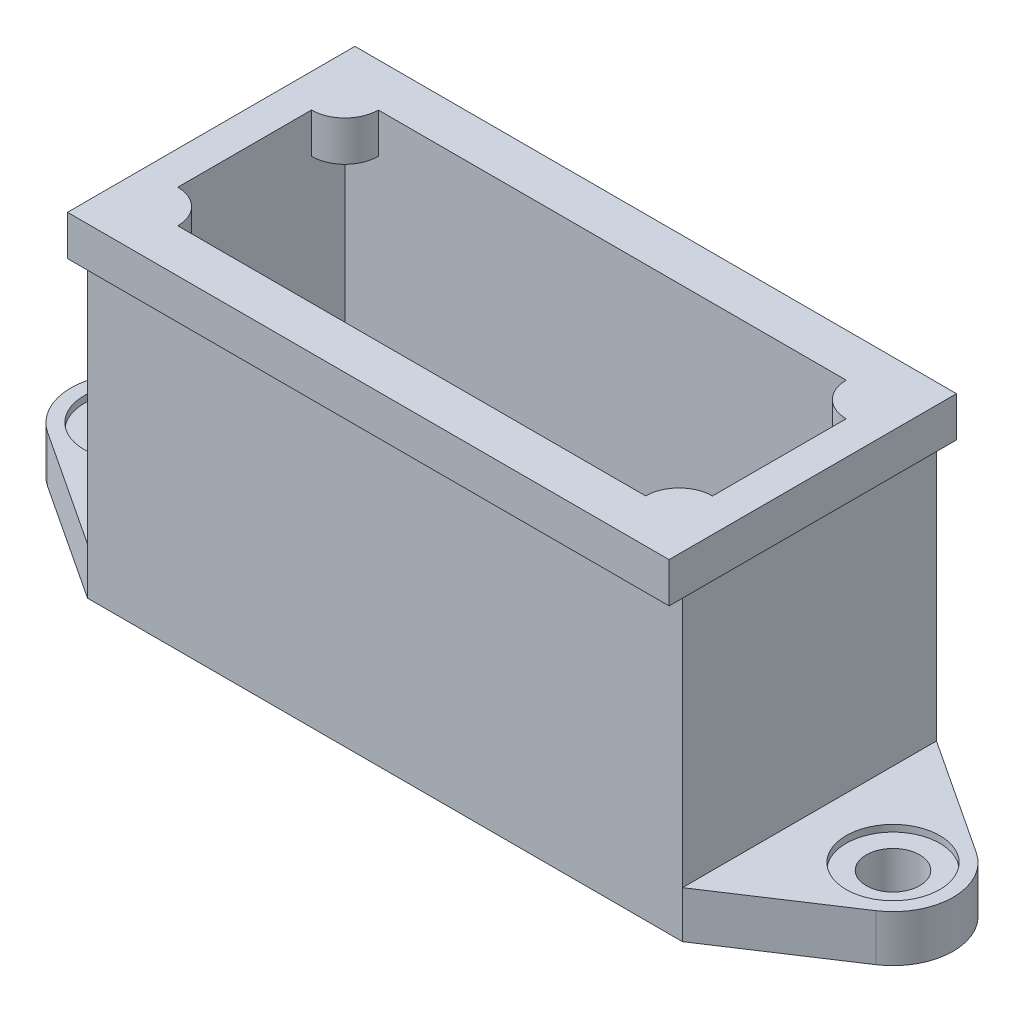
SolidWorks part; units mm, degrees
ref_plane "Front Plane" through (0, 0, 0) normal (0, 0, 1) x (1, 0, 0)
ref_plane "Top Plane" through (0, 0, 0) normal (0, 1, 0) x (1, 0, 0)
ref_plane "Right Plane" through (0, 0, 0) normal (1, 0, 0) x (0, 0, -1)
sketch "Sketch1" plane through (0, 0, 0) normal (0, 1, 0) x (1, 0, 0)
  line L1 (-89, -38) -> (89, -38)
  line L2 (-89, -38) -> (-89, 38)
  line L3 (-89, 38) -> (89, 38)
  line L4 (89, -38) -> (89, 38)
  line L5 (-89, -38) -> (89, 38) construction
  line L6 (-89, 38) -> (89, -38) construction
  point P0 (0, 0)
  dimension "D1" = 76
  dimension "D2" = 178
extrude "Boss-Extrude1" add sketch "Sketch1" along normal blind 90
sketch "Sketch2" plane through (0, 0, 0) normal (0, 1, 0) x (1, 0, 0)
  line L0 (0, 0) -> (136.8069, 0) construction
  line L1 (123.8951, 15.0362) -> (89, 38)
  line L2 (123.8951, -15.0362) -> (89, -38)
  line L3 (89, 38) -> (89, -38)
  arc A0 (123.8951, -15.0362) -> (123.8951, 15.0362) centre (114, 0) ccw
  dimension "D2" = 36
  dimension "D1" = 114
extrude "Boss-Extrude2" add sketch "Sketch2" along normal blind 14
hole_wizard "CBORE for M14 Hex Head Bolt1" positions "3DSketch1" profile "Sketch3" counterbore size "M14" standard "ANSI Metric" end condition through all
sketch3d "3DSketch1"
  line L0 (114, 14, 0) -> (114, 0, 0) construction
  point P0 (114, 14, 0)
sketch "Sketch3" plane through (114, 14, 0) normal (1, 0, 0) x (0, 0, 1)
  line L0 (0, 0) -> (0, 14)
  line L1 (0, 14) -> (8, 14)
  line L3 (8, 14) -> (8, 2)
  line L4 (8, 2) -> (14, 2)
  line L5 (14, 2) -> (14, 0)
  line L7 (14, 0) -> (0, 0)
  line L11 (0, -6.35) -> (0, 107.95) construction
  dimension "Thru Hole Dia." = 16
  dimension "Thru Hole Depth" = 14
  dimension "C'Bore Dia." = 28
  dimension "C'Bore Depth" = 2
mirror "Mirror1" about plane through (0, 0, 0) normal (1, 0, 0) of "Boss-Extrude2", "CBORE for M14 Hex Head Bolt1"
sketch "Sketch4" plane through (0, 90, 0) normal (0, 1, 0) x (1, 0, 0)
  line L1 (-80, -30) -> (80, -30)
  line L2 (-80, -30) -> (-80, 30)
  line L3 (-80, 30) -> (80, 30)
  line L4 (80, -30) -> (80, 30)
  line L5 (-80, -30) -> (80, 30) construction
  line L6 (-80, 30) -> (80, -30) construction
  point P0 (0, 0)
  dimension "D1" = 160
  dimension "D2" = 60
extrude "Cut-Extrude1" cut sketch "Sketch4" against normal blind 63
sketch "Sketch5" plane through (0, 90, 0) normal (0, 1, 0) x (1, 0, 0)
  line L0 (0, -30) -> (0, 30) construction
  line L1 (-90, -43) -> (90, -43)
  line L2 (-90, -43) -> (-90, 43)
  line L3 (-90, 43) -> (90, 43)
  line L4 (90, -43) -> (90, 43)
  line L5 (-90, -43) -> (90, 43) construction
  line L6 (-90, 43) -> (90, -43) construction
  line L7 (-70, -30) -> (70, -30)
  line L9 (-70, 30) -> (70, 30)
  line L11 (-80, -30) -> (80, 30) construction
  line L12 (-80, 30) -> (80, -30) construction
  line L13 (80, -20) -> (80, 20)
  line L14 (-80, 30) -> (-80, -30) construction
  line L15 (-80, -20) -> (-80, 20)
  arc A0 (-80, 20) -> (-70, 30) centre (-80, 30) ccw
  arc A2 (-70, -30) -> (-80, -20) centre (-80, -30) ccw
  arc A3 (80, 20) -> (70, 30) centre (80, 30) cw
  arc A4 (70, -30) -> (80, -20) centre (80, -30) cw
  point P0 (0, 0)
  point P6 (0, 0)
  point P20 (-80, 20)
  point P21 (0, 0)
  point P22 (69.6535, -27.4241)
  point P24 (-80, 28.4243)
  point P25 (-69.9223, 30)
  point P26 (-64.2681, 30)
  point P29 (-80.8026, 28.8707)
  point P32 (-80, -20)
  point P33 (-80, -20)
  point P34 (-80, 20)
  dimension "D5" = 20
  dimension "D6" = 10
  dimension "D1" = 86
  dimension "D2" = 180
  dimension "D3" = 160
  dimension "D4" = 60
  dimension "D7" = 30
  dimension "D8" = 0
  dimension "D9" = 0
extrude "Boss-Extrude4" add sketch "Sketch5" along normal blind 12
